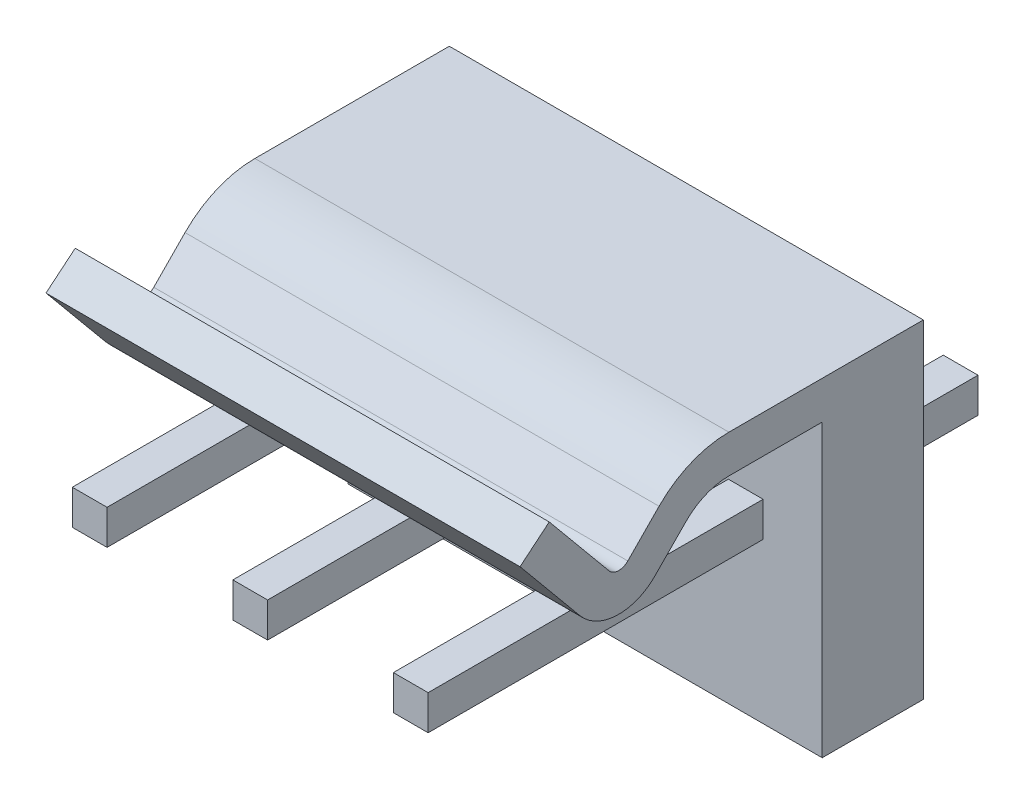
SolidWorks part; units mm, degrees
ref_plane "Front" through (0, 0, 0) normal (0, 0, 1) x (1, 0, 0)
ref_plane "Top" through (0, 0, 0) normal (0, 1, 0) x (1, 0, 0)
ref_plane "Right" through (0, 0, 0) normal (1, 0, 0) x (0, 0, -1)
sketch "Эскиз1" plane through (0, 0, 0) normal (0, 0, 1) x (1, 0, 0)
  line L1 (-1.4, -1.4) -> (1.4, -1.4)
  line L2 (-1.4, -1.4) -> (-1.4, 1.4)
  line L3 (-1.4, 1.4) -> (1.4, 1.4)
  line L4 (1.4, -1.4) -> (1.4, 1.4)
  line L5 (8.76, -1.4) -> (11.56, -1.4)
  line L6 (8.76, -1.4) -> (8.76, 1.4)
  line L7 (8.76, 1.4) -> (11.56, 1.4)
  line L8 (11.56, -1.4) -> (11.56, 1.4)
  line L9 (3.68, -1.4) -> (6.48, -1.4)
  line L10 (3.68, -1.4) -> (3.68, 1.4)
  line L11 (3.68, 1.4) -> (6.48, 1.4)
  line L12 (6.48, -1.4) -> (6.48, 1.4)
sketch "Эскиз2" plane through (0, 0, 0) normal (0, 0, 1) x (1, 0, 0)
  line L0 (-2.42, 4.8) -> (-2.42, -5.6)
  line L1 (12.58, -5.6) -> (12.58, 4.8)
  line L2 (-2.42, -5.6) -> (12.58, -5.6)
  line L4 (12.58, 4.8) -> (-2.42, 4.8)
  dimension "D1" = 2.42
  dimension "D2" = 4.8
  dimension "D3" = 15
  dimension "D4" = 5.6
extrude "Вытянуть1" add sketch "Эскиз2" along normal blind 3.2
sketch "Эскиз3" plane through (0, 0, 0) normal (0, 0, 1) x (1, 0, 0)
  line L0 (0, 0) -> (0, -0.55) construction
  line L1 (-0.55, 0.55) -> (0.55, 0.55)
  line L2 (-0.55, 0.55) -> (-0.55, -0.55)
  line L3 (-0.55, -0.55) -> (0.55, -0.55)
  line L4 (0.55, 0.55) -> (0.55, -0.55)
  line L5 (0, -0.55) -> (0, 0) construction
  line L6 (0, 0) -> (-0.55, 0) construction
  line L7 (4.53, 0.55) -> (5.63, 0.55)
  line L8 (4.53, 0.55) -> (4.53, -0.55)
  line L9 (4.53, -0.55) -> (5.63, -0.55)
  line L10 (5.63, 0.55) -> (5.63, -0.55)
  line L11 (9.61, 0.55) -> (10.71, 0.55)
  line L12 (9.61, 0.55) -> (9.61, -0.55)
  line L13 (9.61, -0.55) -> (10.71, -0.55)
  line L14 (10.71, 0.55) -> (10.71, -0.55)
  dimension "D1" = 1.1
  dimension "D2" = 1.1
  dimension "D3" = 5.08
extrude "Вытянуть2" add sketch "Эскиз3" along normal blind 13.8 and the other way blind 3.6
sketch "Эскиз4" plane through (-2.42, 0, 0) normal (-1, 0, 0) x (0, 0, 1)
  line L0 (3.2, 4.2) -> (6.1526, 4.2)
  line L1 (3.2, 4.8) -> (3.2, -5.6) construction
  line L2 (7.9346, 3.4534) -> (8.9232, 2.4487)
  line L3 (10.4063, 2.5123) -> (12.3, 4.8)
  line L4 (0, 4.8) -> (0, -5.6) construction
  line L5 (3.2, 4.8) -> (0, 4.8) construction
  line L7 (3.2, 0.55) -> (13.8, 0.55) construction
  arc A0 (6.1526, 4.2) -> (7.9346, 3.4534) centre (6.1526, 1.7) cw
  arc A1 (8.9232, 2.4487) -> (10.4063, 2.5123) centre (9.636, 3.15) ccw
  point P15 (7.2, 4.2)
  point P17 (9.7, 1.6591)
  dimension "D6" = 2.5
  dimension "D7" = 1
  dimension "D4" = 1.6
  dimension "D1" = 12.3
  dimension "D2" = 0.6
  dimension "D3" = 6.5
  dimension "D5" = 4
sketch "Эскиз5" plane through (0, 0, 3.2) normal (0, 0, 1) x (1, 0, 0)
  line L0 (12.58, -5.6) -> (12.58, 4.8) construction
  line L1 (-2.42, 4.8) -> (12.58, 4.8)
  line L2 (-2.42, 4.8) -> (-2.42, 3.6)
  line L3 (-2.42, 3.6) -> (12.58, 3.6)
  line L4 (12.58, 4.8) -> (12.58, 3.6)
  dimension "D1" = 1.2
sweep "По траектории1" add profiles "Эскиз5" path "Эскиз4"
sketch "Эскиз6" plane through (0, 0, -3.6) normal (0, 0, -1) x (-1, 0, 0)
  circle A0 centre (0, 0) radius 0.3255
extrude "Вырез-Вытянуть1" cut sketch "Эскиз6" against normal blind 2
